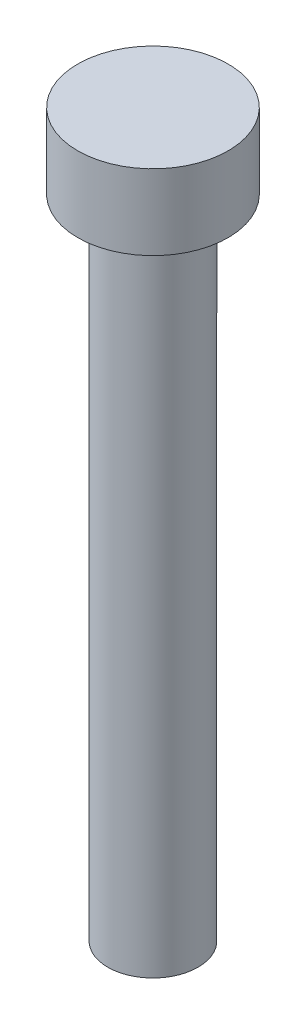
SolidWorks part; units mm, degrees
ref_plane "Front Plane" through (0, 0, 0) normal (0, 0, 1) x (1, 0, 0)
ref_plane "Top Plane" through (0, 0, 0) normal (0, 1, 0) x (1, 0, 0)
ref_plane "Right Plane" through (0, 0, 0) normal (1, 0, 0) x (0, 0, -1)
sketch "Sketch2" plane through (0, 0, 0) normal (0, 1, 0) x (1, 0, 0)
  circle A0 centre (0, 0) radius 3.048
extrude "Boss-Extrude1" add sketch "Sketch2" along normal blind 29.718 and the other way blind 8.89
sketch "Sketch3" plane through (0, 29.718, 0) normal (0, 1, 0) x (1, 0, 0)
  circle A0 centre (0, 0) radius 5.08
extrude "Boss-Extrude2" add sketch "Sketch3" along normal blind 5.08
sketch "Sketch4" plane through (0, -8.89, 0) normal (0, -1, 0) x (1, 0, 0)
  circle A0 centre (0, 0) radius 3.048
extrude "Boss-Extrude3" add sketch "Sketch4" along normal blind 5.08
